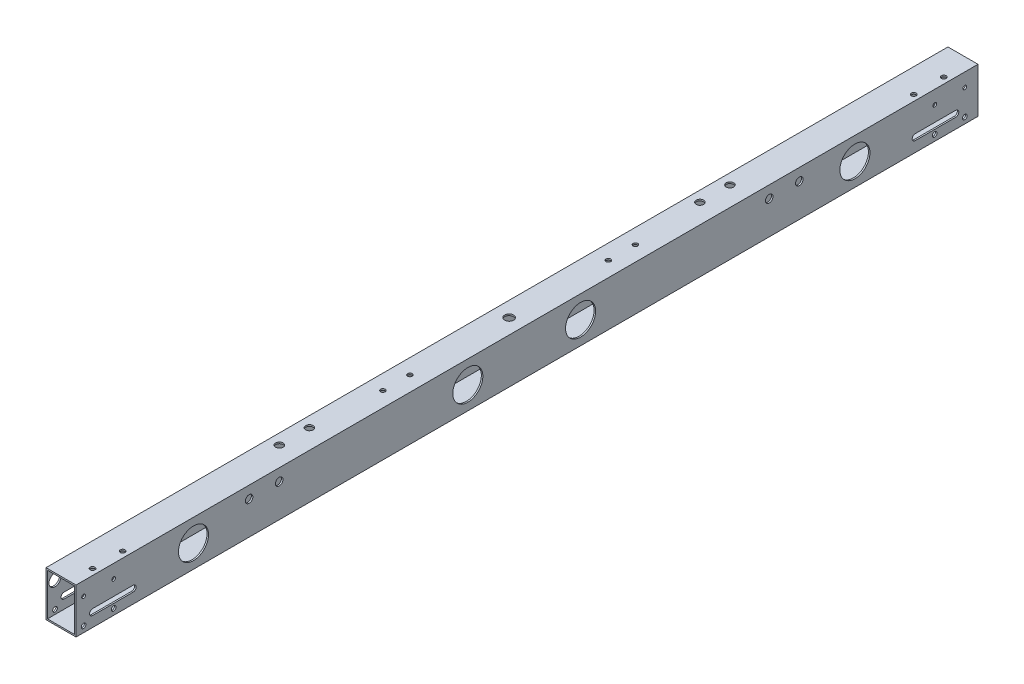
SolidWorks part; units mm, degrees
material "6061 合金"
ref_plane "前视基准面" through (0, 0, 0) normal (0, 0, 1) x (1, 0, 0)
ref_plane "上视基准面" through (0, 0, 0) normal (0, 1, 0) x (1, 0, 0)
ref_plane "右视基准面" through (0, 0, 0) normal (1, 0, 0) x (0, 0, -1)
other "Configuration Table"
sketch "草图1" plane through (0, 0, 0) normal (0, 0, 1) x (1, 0, 0)
  line L1 (-10, 15) -> (10, 15)
  line L2 (-10, 15) -> (-10, -15)
  line L3 (-10, -15) -> (10, -15)
  line L4 (10, 15) -> (10, -15)
  line L5 (-10, 15) -> (10, -15) construction
  line L6 (-10, -15) -> (10, 15) construction
  line L7 (-9, 14) -> (9, 14)
  line L8 (-9, 14) -> (-9, -14)
  line L9 (-9, -14) -> (9, -14)
  line L10 (9, 14) -> (9, -14)
  line L11 (-9, 14) -> (9, -14) construction
  line L12 (-9, -14) -> (9, 14) construction
  point P0 (0, 0)
  point P6 (0, 0)
  dimension "D1" = 1
  dimension "D2" = 20
  dimension "D3" = 30
  dimension "D4" = 1
extrude "凸台-拉伸1" add sketch "草图1" along normal blind 600
sketch "草图2" plane through (0, 15, 0) normal (0, 1, 0) x (1, 0, 0)
  line L0 (0, -367.88) -> (0, -235.88) construction
  circle A0 centre (0, -217.88) radius 1.55
  circle A1 centre (0, -235.88) radius 1.55
  circle A2 centre (0, -367.88) radius 1.55
  circle A3 centre (0, -385.88) radius 1.55
  circle A4 centre (0, -301.88) radius 3
  point P16 (0, -301.88)
  dimension "D1" = 3.1
  dimension "D2" = 6
extrude "切除-拉伸1" cut sketch "草图2" against normal blind 5
sketch "草图3" plane through (0, 15, 0) normal (0, 1, 0) x (1, 0, 0)
  circle A0 centre (0, -385.88) radius 1.55
  circle A1 centre (0, -367.88) radius 1.55
  circle A2 centre (0, -235.88) radius 1.55
  circle A3 centre (0, -217.88) radius 1.55
  dimension "D1" = 3.1
sketch "草图5" plane through (0, -14, 0) normal (0, 1, 0) x (1, 0, 0)
  circle A0 centre (0, -385.88) radius 5
  circle A1 centre (0, -367.88) radius 5
  circle A2 centre (0, -235.88) radius 5
  circle A3 centre (0, -217.88) radius 5
  dimension "D1" = 10
extrude "切除-拉伸6" cut sketch "草图5" against normal blind 10
sketch "草图7" plane through (10, 0, 0) normal (1, 0, 0) x (0, 0, -1)
  line L0 (-589, -5) -> (-589, -8) construction
  line L1 (-14.76, -5) -> (-14.76, -8) construction
  line L7 (-589, -5) -> (-589, -8) construction
  line L8 (-14.76, -5) -> (-14.76, -8) construction
  line L14 (-14.76, -4.1) -> (-41.76, -4.1)
  line L15 (-14.76, -4.1) -> (-14.76, -8.1)
  line L16 (-14.76, -8.1) -> (-41.76, -8.1)
  line L17 (-41.76, -4.1) -> (-41.76, -8.1)
  line L18 (-589, -4.1) -> (-562, -4.1)
  line L19 (-589, -4.1) -> (-589, -8.1)
  line L20 (-589, -8.1) -> (-562, -8.1)
  line L21 (-562, -4.1) -> (-562, -8.1)
  circle A12 centre (-14.76, -6.1) radius 2
  circle A13 centre (-41.76, -6.1) radius 2
  circle A16 centre (-589, -6.1) radius 2
  circle A17 centre (-562, -6.1) radius 2
  circle A18 centre (-8.76, 6) radius 1.25 construction
  circle A19 centre (-8.76, 6) radius 1.25
  circle A20 centre (-28.76, 6) radius 1.25 construction
  circle A21 centre (-28.76, 6) radius 1.25
  circle A22 centre (-595, 6) radius 1.25 construction
  circle A23 centre (-595, 6) radius 1.25
  circle A24 centre (-575, 6) radius 1.25 construction
  circle A25 centre (-575, 6) radius 1.25
  dimension "D1" = 0.9
  dimension "D4" = 0.9
  dimension "D5" = 4
  dimension "D6" = 27
  dimension "D7" = 4
  dimension "D8" = 27
extrude "切除-拉伸7" cut sketch "草图7" against normal blind 25 contours L19 A16 | L19 A16 | A17 L18 A16 L20 | A23 | L21 A17 | L21 A17 | L17 A13 | L17 A13 | A13 L16 A12 L14 | L15 A12 | L15 A12 | A25 | A19 | A21
sketch "草图8" plane through (-10, 0, 0) normal (-1, 0, 0) x (0, 0, 1)
  circle A4 centre (8.76, 6) radius 4
  circle A5 centre (28.76, 6) radius 4
  circle A6 centre (575, 6) radius 4
  circle A7 centre (595, 6) radius 4
  dimension "D1" = 8
extrude "切除-拉伸8" cut sketch "草图8" against normal blind 3
sketch "草图10" plane through (0, 15, 0) normal (0, 1, 0) x (1, 0, 0)
  circle A4 centre (6, -585) radius 1.6
  circle A5 centre (6, -565) radius 1.6
  circle A6 centre (6, -38.76) radius 1.6
  circle A7 centre (6, -18.76) radius 1.6
  dimension "D1" = 3.2
extrude "切除-拉伸9" cut sketch "草图10" against normal blind 40
sketch "草图11" plane through (0, -15, 0) normal (0, -1, 0) x (1, 0, 0)
  line L0 (-10, 600) -> (-10, 0) construction
  circle A0 centre (-3, 152) radius 2.5
  circle A2 centre (-3, 172) radius 2.5
  dimension "D1" = 5
  dimension "D2" = 20
  dimension "D3" = 7
  dimension "D4" = 152
extrude "切除-拉伸10" cut sketch "草图11" against normal blind 40
sketch "草图13" plane through (0, -15, 0) normal (0, -1, 0) x (1, 0, 0)
  circle A0 centre (-3, 431.76) radius 2.5
  circle A1 centre (-3, 451.76) radius 2.5
  dimension "D1" = 5
extrude "切除-拉伸11" cut sketch "草图13" against normal blind 40
sketch "草图14" plane through (0, -14, 0) normal (0, 1, 0) x (1, 0, 0)
  line L0 (0, -291.88) -> (0, -311.88) construction
  line L1 (6, -291.88) -> (6, -311.88)
  line L2 (-6, -291.88) -> (-6, -311.88)
  arc A0 (6, -291.88) -> (-6, -291.88) centre (0, -291.88) ccw
  arc A1 (-6, -311.88) -> (6, -311.88) centre (0, -311.88) ccw
  point P2 (0, -301.88)
  dimension "D2" = 6
  dimension "D1" = 20
extrude "切除-拉伸12" cut sketch "草图14" against normal blind 10
sketch "草图16" plane through (-10, 0, 0) normal (-1, 0, 0) x (0, 0, 1)
  circle A0 centre (464.88, 7) radius 2.5
  circle A1 centre (484.88, 7) radius 2.5
  dimension "D1" = 5
extrude "切除-拉伸13" cut sketch "草图16" against normal blind 50
sketch "草图17" plane through (-10, 0, 0) normal (-1, 0, 0) x (0, 0, 1)
  circle A0 centre (118.88, 7) radius 2.5
  circle A1 centre (138.88, 7) radius 2.5
  dimension "D1" = 5
extrude "切除-拉伸14" cut sketch "草图17" against normal blind 50
sketch "草图18" plane through (10, 0, 0) normal (1, 0, 0) x (0, 0, -1)
  circle A0 centre (-28.76, -11) radius 1.55
  circle A1 centre (-8.76, -11) radius 1.55
  dimension "D1" = 3.1
extrude "切除-拉伸15" cut sketch "草图18" against normal blind 40
sketch "草图19" plane through (10, 0, 0) normal (1, 0, 0) x (0, 0, -1)
  circle A1 centre (-575, -11) radius 1.55
  circle A2 centre (-595, -11) radius 1.55
  dimension "D1" = 3.1
extrude "切除-拉伸16" cut sketch "草图19" against normal blind 40
sketch "草图20" plane through (-10, 0, 0) normal (-1, 0, 0) x (0, 0, 1)
  line L0 (311.88, -15) -> (291.88, -15) construction
  line L1 (311.88, -15) -> (291.88, -15) construction
  line L2 (301.88, -15) -> (301.88, 30.0698) construction
  circle A0 centre (81.88, 0) radius 10
  circle A1 centre (264.38, 0) radius 10
  circle A2 centre (339.38, 0) radius 10
  circle A3 centre (196.88, 0) radius 10 construction
  circle A4 centre (406.88, 0) radius 10 construction
  circle A5 centre (521.88, 0) radius 10
  dimension "D1" = 20
  dimension "D3" = 20
  dimension "D2" = 220
  dimension "D4" = 75
  dimension "D5" = 105
extrude "切除-拉伸17" cut sketch "草图20" against normal blind 40
